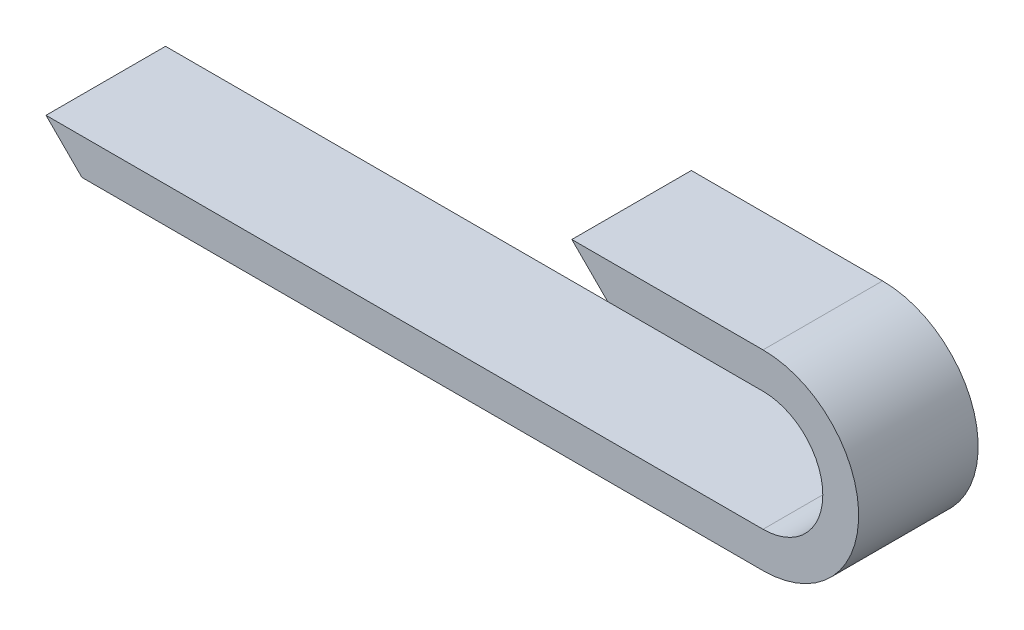
SolidWorks part; units mm, degrees
ref_plane "前视基准面" through (0, 0, 0) normal (0, 0, 1) x (1, 0, 0)
ref_plane "上视基准面" through (0, 0, 0) normal (0, 1, 0) x (1, 0, 0)
ref_plane "右视基准面" through (0, 0, 0) normal (1, 0, 0) x (0, 0, -1)
sketch "草图1" plane through (0, 0, 0) normal (0, 0, 1) x (1, 0, 0)
  line L0 (111.3001, 44.9564) -> (126.3001, 29.9564)
  line L1 (-108.6999, -20.0436) -> (191.3001, -20.0436)
  line L5 (191.3001, 44.9564) -> (111.3001, 44.9564)
  line L6 (191.3001, 29.9564) -> (126.3001, 29.9564)
  line L7 (191.3001, -35.0436) -> (-93.6999, -35.0436)
  line L8 (-93.6999, -35.0436) -> (-108.6999, -20.0436)
  arc A2 (191.3001, 29.9564) -> (191.3001, -20.0436) centre (191.3001, 4.9564) cw
  arc A3 (191.3001, 44.9564) -> (191.3001, -35.0436) centre (191.3001, 4.9564) cw
  point P9 (191.3001, 29.9564)
  dimension "D2" = 300
extrude "凸台-拉伸1" add sketch "草图1" against normal blind 50
scale "缩放比例1" scale about origin uniform scaling yes scale factor 1.7
